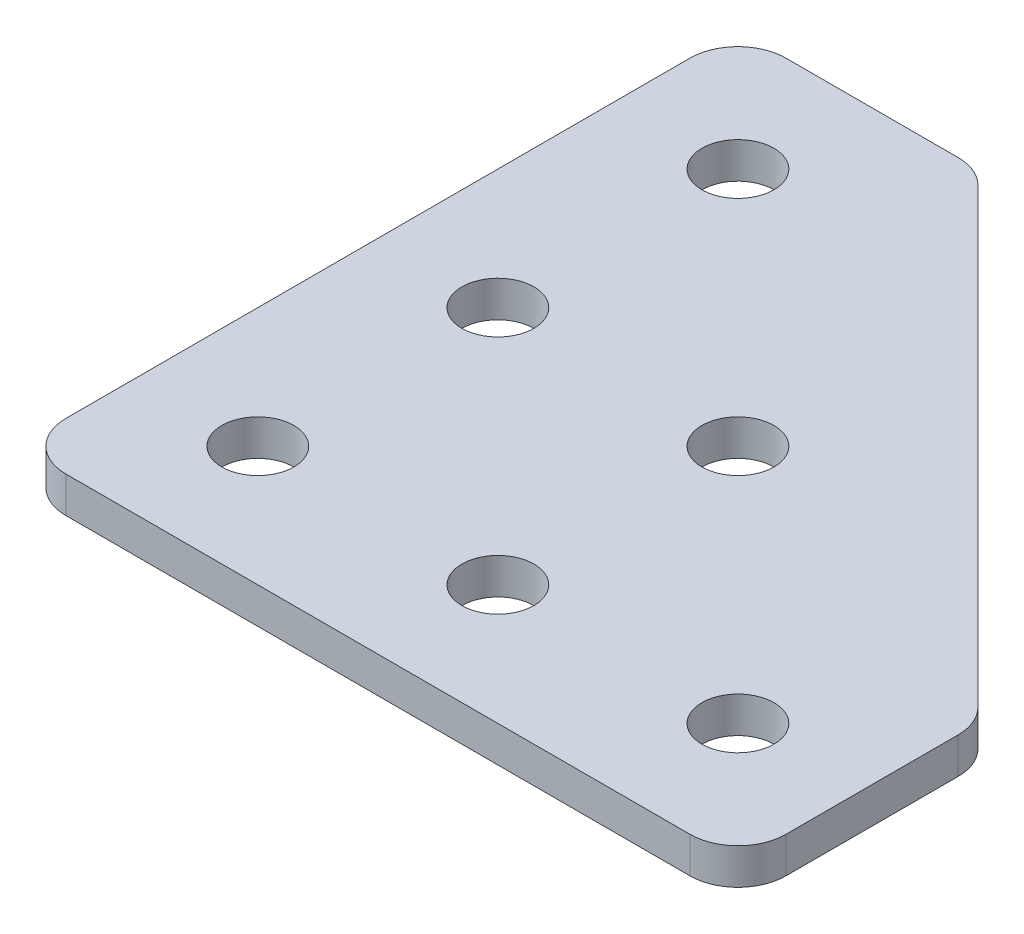
SolidWorks part; units mm, degrees
material "5052-H34"
ref_plane "正面" through (0, 0, 0) normal (0, 0, 1) x (1, 0, 0)
ref_plane "平面" through (0, 0, 0) normal (0, 1, 0) x (1, 0, 0)
ref_plane "右側面" through (0, 0, 0) normal (1, 0, 0) x (0, 0, -1)
sketch "ｽｹｯﾁ2" plane through (0, 0, 0) normal (0, 1, 0) x (1, 0, 0)
  line L0 (0, 0) -> (30, 0)
  line L1 (30, 0) -> (30, 10)
  line L2 (30, 10) -> (10, 30)
  line L3 (10, 30) -> (0, 30)
  line L4 (0, 30) -> (0, 0)
  line L5 (0, 0) -> (20, 20) construction
  line L6 (30, 5) -> (0, 5) construction
  line L7 (5, 25) -> (5, 5) construction
  circle A0 centre (5, 5) radius 1.5
  circle A1 centre (25, 5) radius 1.5
  circle A2 centre (5, 25) radius 1.5
  circle A3 centre (5, 15) radius 1.5
  circle A4 centre (15, 5) radius 1.5
  circle A5 centre (15, 15) radius 1.5
  dimension "D1" = 10
  dimension "D2" = 3
  dimension "D3" = 5
  dimension "D4" = 5
  dimension "D5" = 20
  dimension "D6" = 10
extrude "ﾎﾞｽ - 押し出し1" add sketch "ｽｹｯﾁ2" along normal blind 1.5
fillet "ﾌｨﾚｯﾄ1" radius 2 5 edges at (0, 0.75, 0) (30, 0.75, 0) (30, 0.75, -10) (10, 0.75, -30) (0, 0.75, -30)
